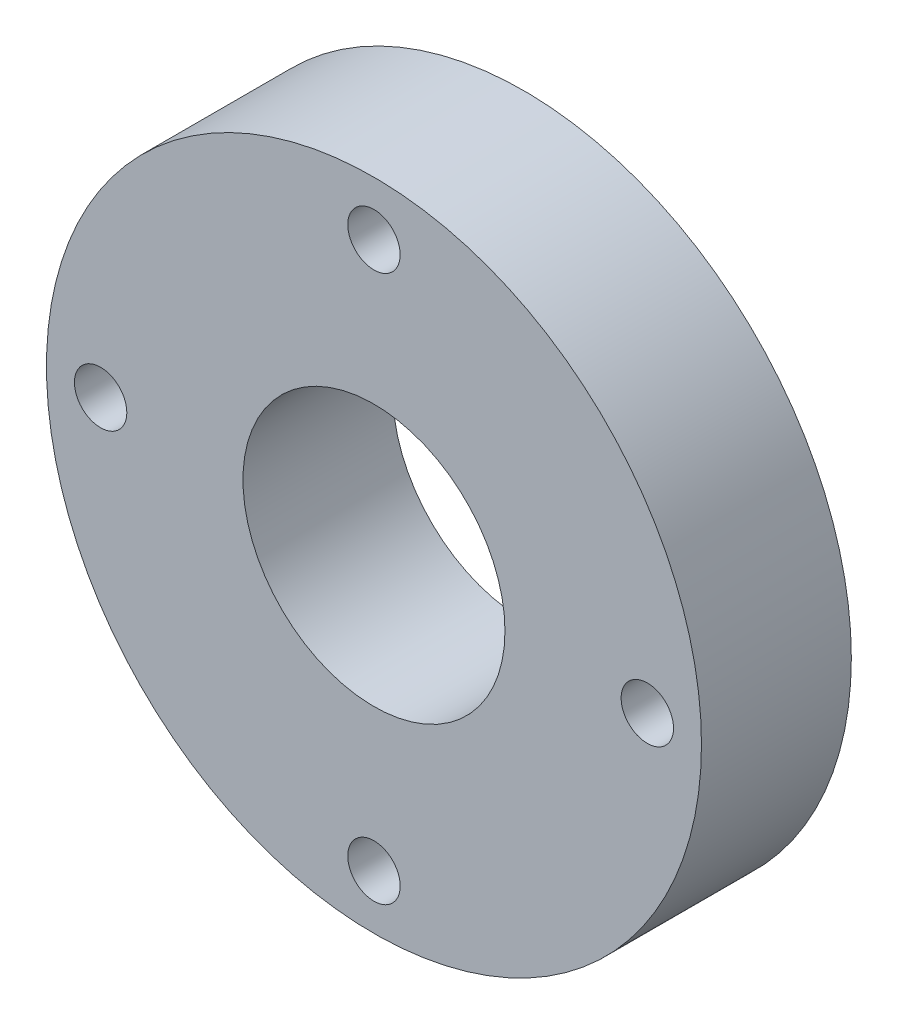
SolidWorks part; units mm, degrees
ref_plane "Front Plane" through (0, 0, 0) normal (0, 0, 1) x (1, 0, 0)
ref_plane "Top Plane" through (0, 0, 0) normal (0, 1, 0) x (1, 0, 0)
ref_plane "Right Plane" through (0, 0, 0) normal (1, 0, 0) x (0, 0, -1)
sketch "Sketch1" plane through (0, 0, 0) normal (0, 0, 1) x (1, 0, 0)
  circle A0 centre (0, 0) radius 125
  circle A1 centre (0, 0) radius 50
extrude "Boss-Extrude1" add sketch "Sketch1" along normal blind 57.2
sketch "Sketch2" plane through (0, 0, 57.2) normal (0, 0, 1) x (1, 0, 0)
  line L0 (-145.8498, 0) -> (156.7577, 0) construction
  line L1 (0, -139.5161) -> (0, 135.2937) construction
  circle A0 centre (-104.3292, 0) radius 10
  circle A1 centre (0, 104.3292) radius 10
  circle A2 centre (104.3292, 0) radius 10
  circle A3 centre (0, -104.3292) radius 10
  dimension "D1" = 4
extrude "Cut-Extrude1" cut sketch "Sketch2" against normal blind 57.2
